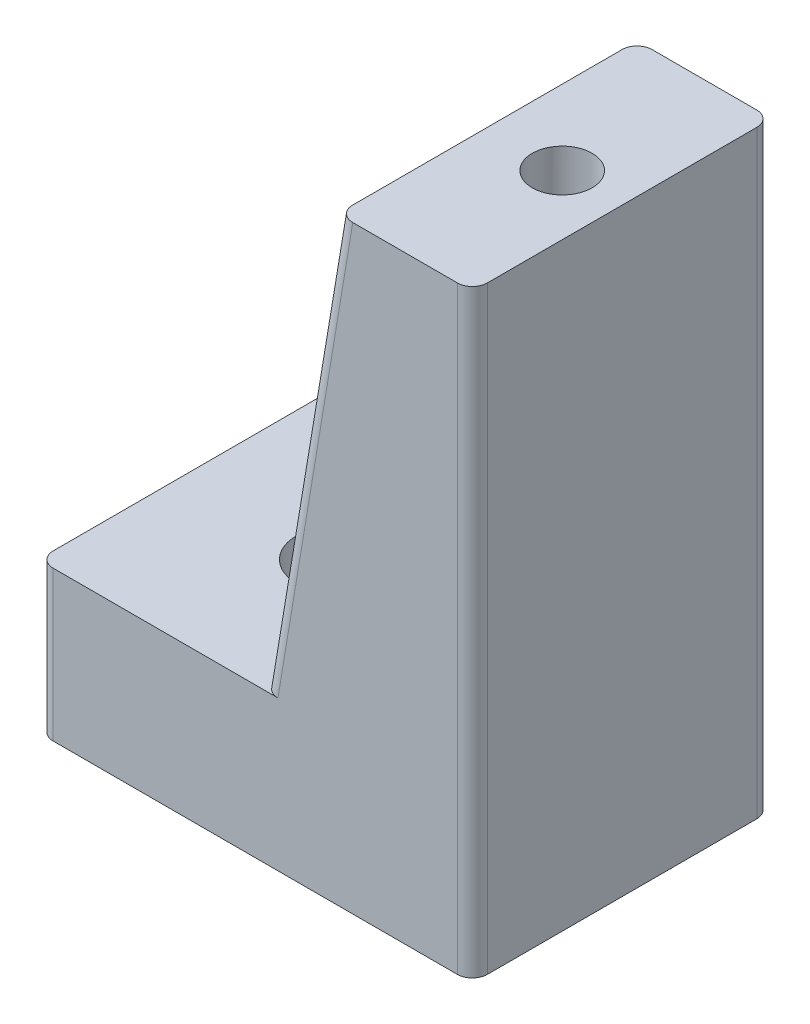
SolidWorks part; units mm, degrees
ref_plane "正面" through (0, 0, 0) normal (0, 0, 1) x (1, 0, 0)
ref_plane "平面" through (0, 0, 0) normal (0, 1, 0) x (1, 0, 0)
ref_plane "右側面" through (0, 0, 0) normal (1, 0, 0) x (0, 0, -1)
sketch "ｽｹｯﾁ1" plane through (0, 0, 0) normal (0, 0, 1) x (1, 0, 0)
  line L0 (0, 0) -> (10, 0)
  line L1 (10, 0) -> (15, 30)
  line L2 (15, 30) -> (24, 30)
  line L3 (24, 30) -> (24, -10)
  line L6 (24, -10) -> (0, -10)
  line L7 (0, -10) -> (0, 0)
  point P3 (54.3937, -10)
  point P6 (3.8574, 0)
  point P7 (54.3937, -8.9286)
  point P10 (17.4184, 30)
  point P11 (10.7593, 0)
  dimension "D1" = 10
  dimension "D2" = 40
  dimension "D3" = 24
  dimension "D4" = 10
  dimension "D5" = 9
extrude "ﾎﾞｽ - 押し出し1" add sketch "ｽｹｯﾁ1" along normal blind 20
sketch "ｽｹｯﾁ2" plane through (0, 30, 0) normal (0, 1, 0) x (1, 0, 0)
  line L0 (0, -10) -> (24, -10) construction
  line L1 (0, -20) -> (0, 0) construction
  line L2 (24, -20) -> (24, 0) construction
  circle A0 centre (20, -10) radius 2
  circle A1 centre (5, -10) radius 2.75
  dimension "D1" = 5.5
  dimension "D4" = 4
  dimension "D2" = 5
  dimension "D3" = 15
extrude "ｶｯﾄ - 押し出し1" cut sketch "ｽｹｯﾁ2" against normal through all
sketch "ｽｹｯﾁ3" plane through (0, -10, 0) normal (0, -1, 0) x (1, 0, 0)
  circle A0 centre (20, 10) radius 2 construction
  circle A1 centre (20, 10) radius 2
extrude "ﾎﾞｽ - 押し出し2" add sketch "ｽｹｯﾁ3" against normal blind 35
sketch "ｽｹｯﾁ4" plane through (0, 0, 0) normal (0, 1, 0) x (1, 0, 0)
  line L0 (10, -20) -> (0, -20) construction
  line L1 (0, 0) -> (-5, 0)
  line L2 (0, 0) -> (0, -20)
  line L3 (0, -20) -> (-5, -20)
  line L4 (-5, 0) -> (-5, -20)
  circle A0 centre (5, -10) radius 2.75 construction
  dimension "D1" = 10
extrude "ﾎﾞｽ - 押し出し3" add sketch "ｽｹｯﾁ4" against normal up to surface (10 mm away) up to face at (5, -10, 12.75)
fillet "ﾌｨﾚｯﾄ2" radius 1 6 edges at (12.5, 15, 0) (12.5, 15, 20) (24, 10, 0) (24, 10, 20) (-5, -5, 20) (-5, -5, 0)
